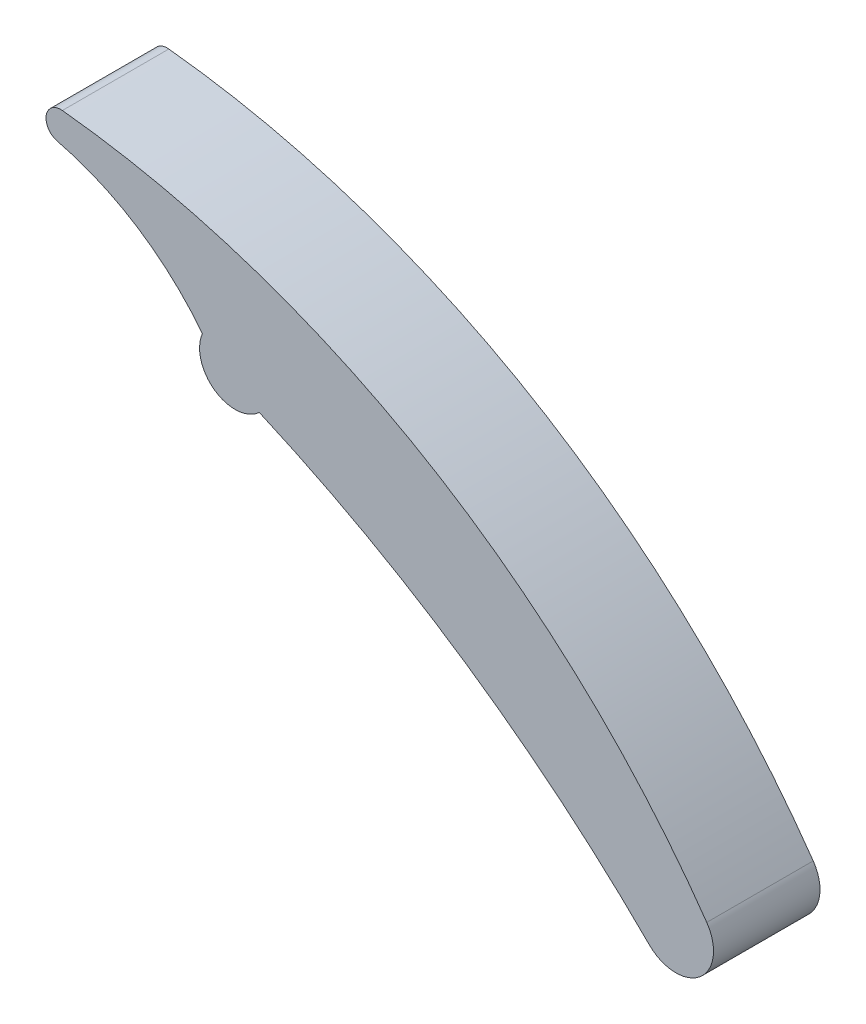
SolidWorks part; units mm, degrees
ref_plane "前视基准面" through (0, 0, 0) normal (0, 0, 1) x (1, 0, 0)
ref_plane "上视基准面" through (0, 0, 0) normal (0, 1, 0) x (1, 0, 0)
ref_plane "右视基准面" through (0, 0, 0) normal (1, 0, 0) x (0, 0, -1)
sketch "草图2" plane through (0, 0, 0) normal (0, 0, 1) x (1, 0, 0)
  arc A0 (-50.1018, 30.4284) -> (-48.6621, 38.6257) centre (-49.1045, 34.4783) cw
  arc A1 (6.8148, -7.3184) -> (-9.2026, 3.9131) centre (0, 0) cw
  arc A2 (-50.1018, 30.4284) -> (-9.2026, 3.9131) centre (-67.8912, -41.812) cw
  arc A3 (-48.6621, 38.6257) -> (132.9212, -68.7182) centre (-75.6375, -214.2615) cw
  arc A4 (132.9212, -68.7182) -> (116.728, -82.2852) centre (124.2255, -74.7866) cw
  arc A5 (6.8148, -7.3184) -> (116.728, -82.2852) centre (-136.6127, -335.6644) cw
  dimension "D3" = 10
  dimension "D4" = 4.1709
  dimension "D5" = 10.6038
  dimension "D6" = 254.3219
  dimension "D1" = 145
  dimension "D2" = 60
extrude "凸台-拉伸1" add sketch "草图2" along normal mid plane 30 contours A2 A1 A5 A4 A3 A0
